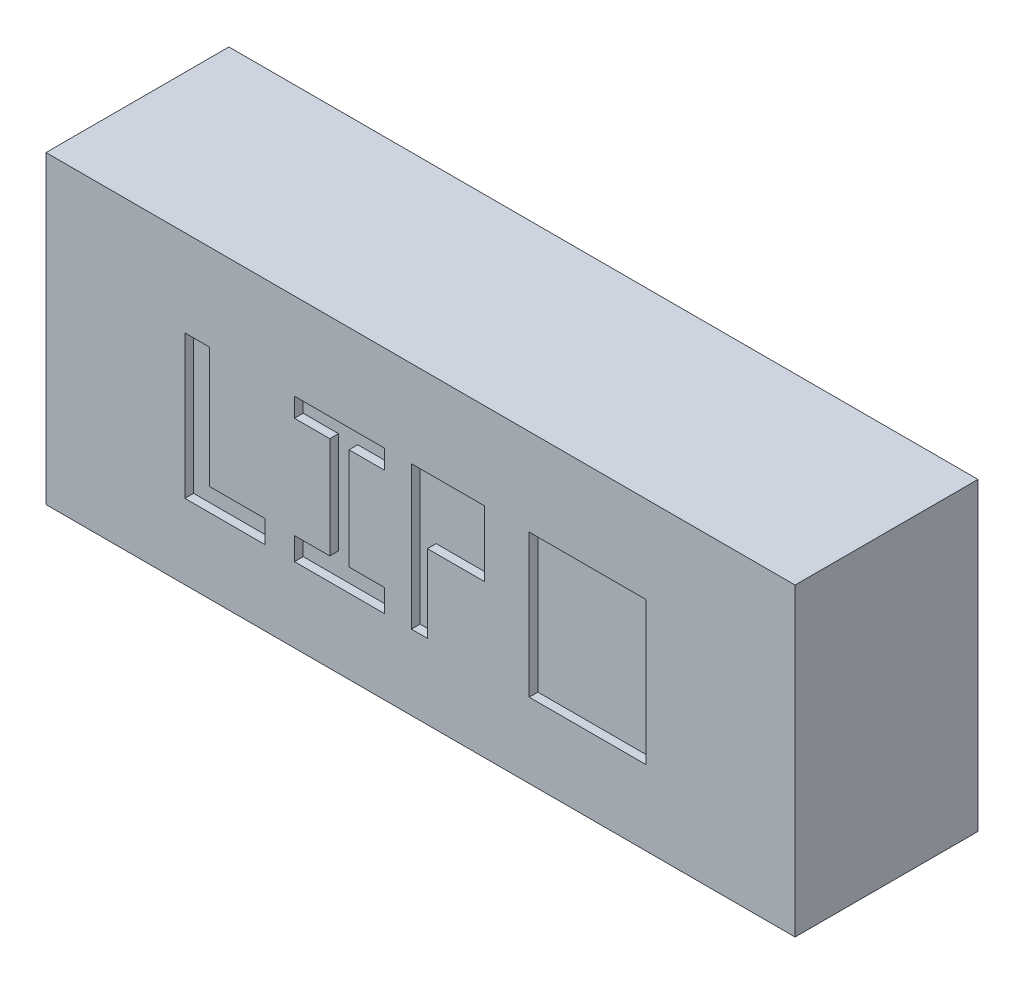
SolidWorks part; units mm, degrees
ref_plane "Front Plane" through (0, 0, 0) normal (0, 0, 1) x (1, 0, 0)
ref_plane "Top Plane" through (0, 0, 0) normal (0, 1, 0) x (1, 0, 0)
ref_plane "Right Plane" through (0, 0, 0) normal (1, 0, 0) x (0, 0, -1)
sketch "Sketch1" plane through (0, 0, 0) normal (0, 1, 0) x (1, 0, 0)
  line L1 (-43, -10.5) -> (43, -10.5)
  line L2 (-43, -10.5) -> (-43, 10.5)
  line L3 (-43, 10.5) -> (43, 10.5)
  line L4 (43, -10.5) -> (43, 10.5)
  line L5 (-43, -10.5) -> (43, 10.5) construction
  line L6 (-43, 10.5) -> (43, -10.5) construction
  point P0 (0, 0)
  dimension "D1" = 21
  dimension "D2" = 86
extrude "Boss-Extrude1" add sketch "Sketch1" along normal blind 35
sketch "Sketch2" plane through (0, 0, 10.5) normal (0, 0, 1) x (1, 0, 0)
  line L0 (-27.0629, 25.0435) -> (-27.0629, 8.5891)
  line L1 (-27.0629, 8.5891) -> (-17.8418, 8.5891)
  line L2 (-17.8418, 8.5891) -> (-17.8418, 11.1842)
  line L3 (-17.8418, 11.1842) -> (-24.2469, 11.1842)
  line L4 (-24.2469, 11.1842) -> (-24.2469, 25.0435)
  line L5 (-24.2469, 25.0435) -> (-27.0629, 25.0435)
  line L6 (-14.4721, 25.0435) -> (-4.1553, 25.0435)
  line L7 (-4.1553, 25.0435) -> (-4.1553, 22.8428)
  line L8 (-14.4721, 25.0435) -> (-14.4721, 22.8428)
  line L9 (-14.4721, 22.8428) -> (-10.4196, 22.8428)
  line L10 (-10.4196, 22.8428) -> (-10.4196, 11.1842)
  line L11 (-10.4196, 11.1842) -> (-14.4721, 11.1842)
  line L12 (-14.4721, 11.1842) -> (-14.4721, 8.5891)
  line L13 (-14.4721, 8.5891) -> (-4.1553, 8.5891)
  line L14 (-4.1553, 8.5891) -> (-4.1553, 11.1842)
  line L15 (-4.1553, 11.1842) -> (-8.2078, 11.1842)
  line L16 (-8.2078, 11.1842) -> (-8.2078, 22.8428)
  line L17 (-8.2078, 22.8428) -> (-4.1553, 22.8428)
  line L18 (-9.3137, 26.4799) -> (-9.3137, 3.9754) construction
  line L19 (-1.0576, 25.0435) -> (-1.0576, 8.5891)
  line L20 (-1.0576, 8.5891) -> (0.7915, 8.5891)
  line L21 (0.7915, 8.5891) -> (0.7915, 17.5143)
  line L22 (0.7915, 17.5143) -> (7.3311, 17.5143)
  line L23 (7.3311, 17.5143) -> (7.3311, 25.0435)
  line L24 (7.3311, 25.0435) -> (-1.0576, 25.0435)
  line L25 (12.4725, 25.001) -> (12.4725, 8.5891)
  line L26 (12.4725, 8.5891) -> (25.8674, 8.5891)
  line L27 (25.8674, 8.5891) -> (25.8674, 25.001)
  line L28 (25.8674, 25.001) -> (12.4725, 25.001)
extrude "Cut-Extrude1" cut sketch "Sketch2" against normal blind 1
